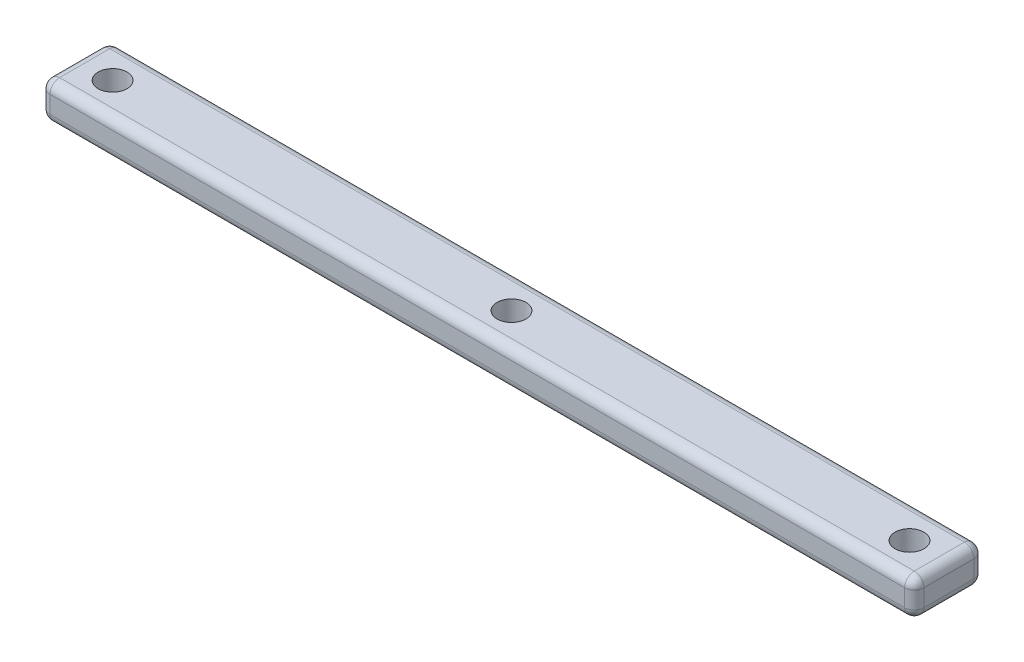
SolidWorks part; units mm, degrees
ref_plane "Front Plane" through (0, 0, 0) normal (0, 0, 1) x (1, 0, 0)
ref_plane "Top Plane" through (0, 0, 0) normal (0, 1, 0) x (1, 0, 0)
ref_plane "Right Plane" through (0, 0, 0) normal (1, 0, 0) x (0, 0, -1)
sketch "Sketch1" plane through (0, 0, 0) normal (0, 1, 0) x (1, 0, 0)
  line L1 (-45.35, 3.6) -> (45.35, 3.6)
  line L2 (-45.35, 3.6) -> (-45.35, -3.6)
  line L3 (-45.35, -3.6) -> (45.35, -3.6)
  line L4 (45.35, 3.6) -> (45.35, -3.6)
  circle A0 centre (-41.35, -0.1) radius 1.5
  circle A1 centre (0.05, -0.1) radius 1.5
  circle A2 centre (41.35, -0.1) radius 1.5
  point P5 (0, 3.6)
  point P6 (45.35, 0)
  point P9 (-45.35, 0)
  point P12 (0, 0)
  dimension "D4" = 3
  dimension "D1" = 90.7
  dimension "D2" = 7.2
  dimension "D3" = 4
  dimension "D5" = 3.7
  dimension "D6" = 41.4
  dimension "D7" = 4
extrude "Boss-Extrude1" add sketch "Sketch1" along normal blind 3.8
fillet "Fillet1" radius 1 12 edges at (-45.35, 1.9, 3.6) (0, 3.8, 3.6) (45.35, 1.9, 3.6) (0, 0, 3.6) (-45.35, 1.9, -3.6) (45.35, 1.9, -3.6) (45.35, 0, 0) (0, 0, -3.6) (-45.35, 0, 0) (45.35, 3.8, 0) (0, 3.8, -3.6) (-45.35, 3.8, 0)
